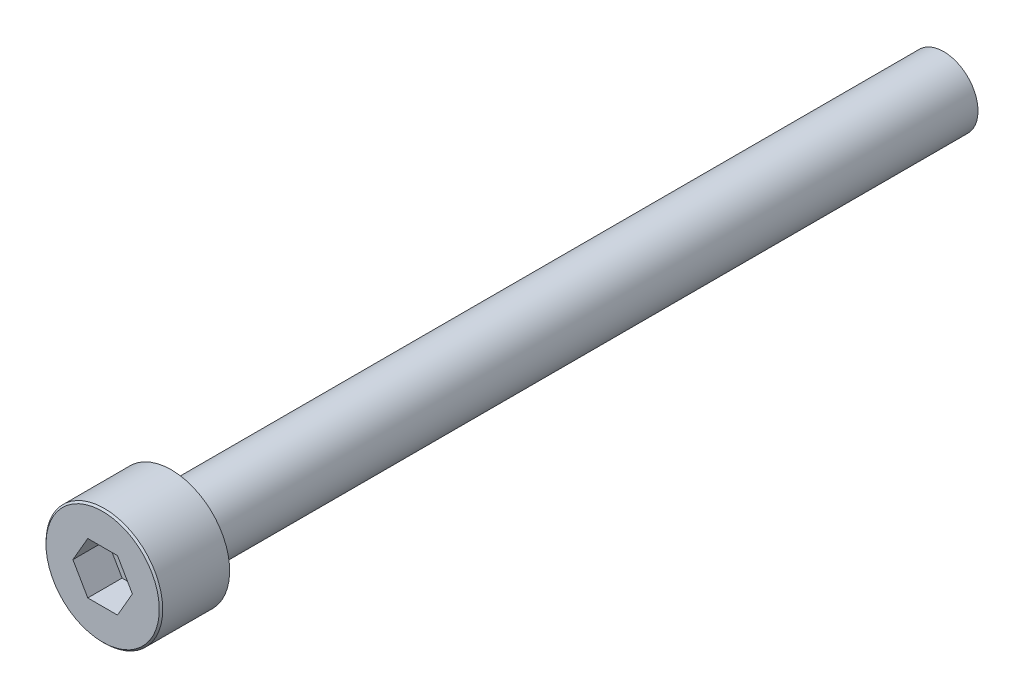
SolidWorks part; units mm, degrees
material "AISI 304"
ref_plane "前视基准面" through (0, 0, 0) normal (0, 0, 1) x (1, 0, 0)
ref_plane "上视基准面" through (0, 0, 0) normal (0, 1, 0) x (1, 0, 0)
ref_plane "右视基准面" through (0, 0, 0) normal (1, 0, 0) x (0, 0, -1)
sketch "草图1" plane through (0, 0, 0) normal (1, 0, 0) x (0, 0, -1)
  line L0 (0, 0) -> (0, 3.4)
  line L1 (0, 3.4) -> (4, 3.4)
  line L2 (4, 3.4) -> (4, 2)
  line L3 (4, 2) -> (49, 2)
  line L4 (49, 2) -> (49, 0)
  line L5 (49, 0) -> (0, 0) construction
  line L6 (0, 0) -> (49, 0)
  dimension "D1" = 6.8
  dimension "D2" = 4
  dimension "D3" = 4
  dimension "D4" = 45
revolve "旋转1" add sketch "草图1" angle 360 about L5
cosmetic thread "装饰螺纹线1" parameters "D2"=2.459
sketch "草图2" plane through (0, 0, 0) normal (0, 0, 1) x (1, 0, 0)
  line L1 (0.866, 1.5) -> (-0.866, 1.5)
  line L2 (-0.866, 1.5) -> (-1.7321, 0)
  line L3 (-1.7321, 0) -> (-0.866, -1.5)
  line L4 (-0.866, -1.5) -> (0.866, -1.5)
  line L5 (0.866, -1.5) -> (1.7321, 0)
  line L6 (1.7321, 0) -> (0.866, 1.5)
  circle A0 centre (0, 0) radius 1.5 construction
  dimension "D1" = 3
extrude "切除-拉伸1" cut sketch "草图2" against normal blind 2
chamfer "装饰倒角" distance 0.1 angle 45 1 edges at (0, 3.4, 0)
